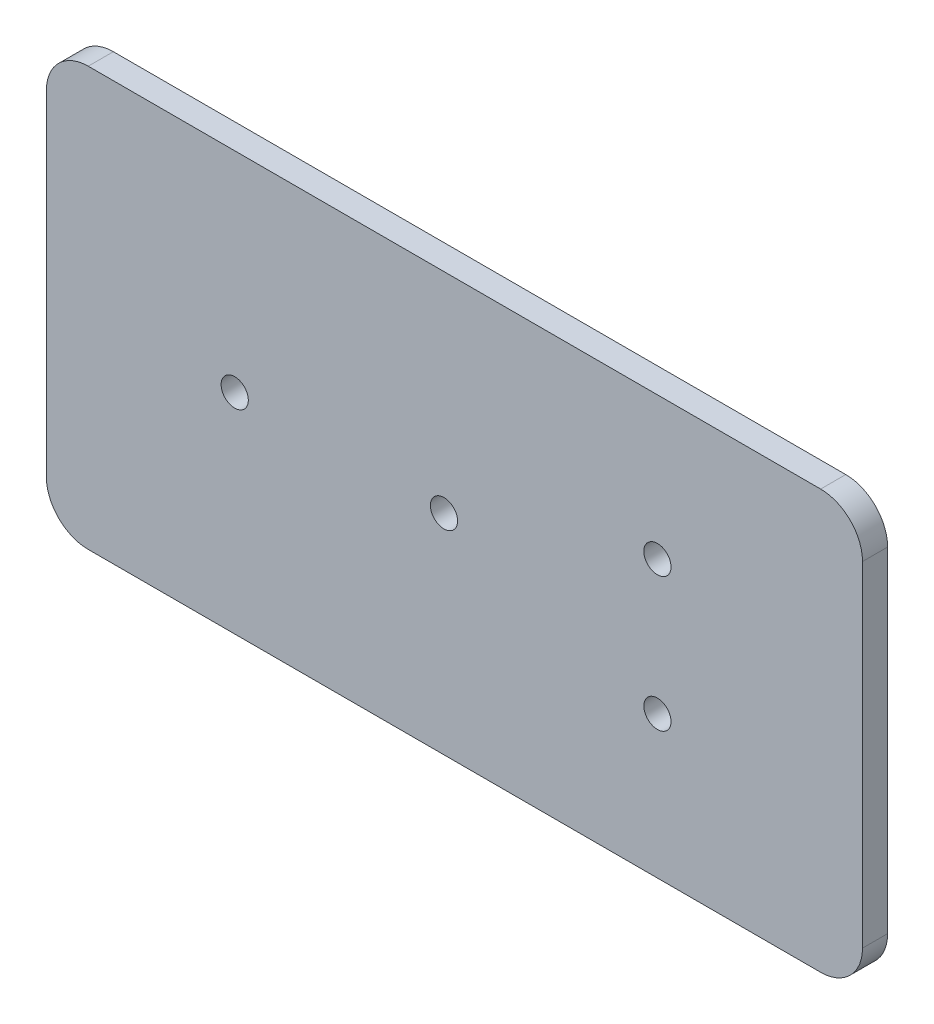
SolidWorks part; units mm, degrees
ref_plane "Front Plane" through (0, 0, 0) normal (0, 0, 1) x (1, 0, 0)
ref_plane "Top Plane" through (0, 0, 0) normal (0, 1, 0) x (1, 0, 0)
ref_plane "Right Plane" through (0, 0, 0) normal (1, 0, 0) x (0, 0, -1)
ref_plane "Plane1" through (0, 0, 5) normal (0, 0, 1) x (1, 0, 0)
sketch "Sketch1" plane through (0, 0, 5) normal (0, 0, 1) x (1, 0, 0)
  line L0 (102.1172, -60.4833) -> (102.1172, 39.5167)
  line L1 (102.1172, 39.5167) -> (-92.8828, 39.5167)
  line L2 (-92.8828, 39.5167) -> (-92.8828, -60.4833)
  line L3 (-92.8828, -60.4833) -> (102.1172, -60.4833)
  line L4 (53.1172, 5.5167) -> (53.1172, -26.4833) construction
  line L5 (102.1172, -10.4833) -> (-92.8828, -10.4833) construction
  circle A0 centre (53.1172, 5.5167) radius 3.25
  circle A1 centre (53.1172, -26.4833) radius 3.25
  circle A2 centre (2.1172, -10.4833) radius 3.25
  circle A3 centre (-47.8828, -10.4833) radius 3.25
  dimension "D3" = 6.5
  dimension "D1" = 49
  dimension "D2" = 32
  dimension "D4" = 100
  dimension "D5" = 150
  dimension "D6" = 100
  dimension "D7" = 195
extrude "Boss-Extrude1" add sketch "Sketch1" against normal blind 6
fillet "Fillet1" radius 10 4 edges at (-92.8828, 39.5167, 2) (-92.8828, -60.4833, 2) (102.1172, 39.5167, 2) (102.1172, -60.4833, 2)
